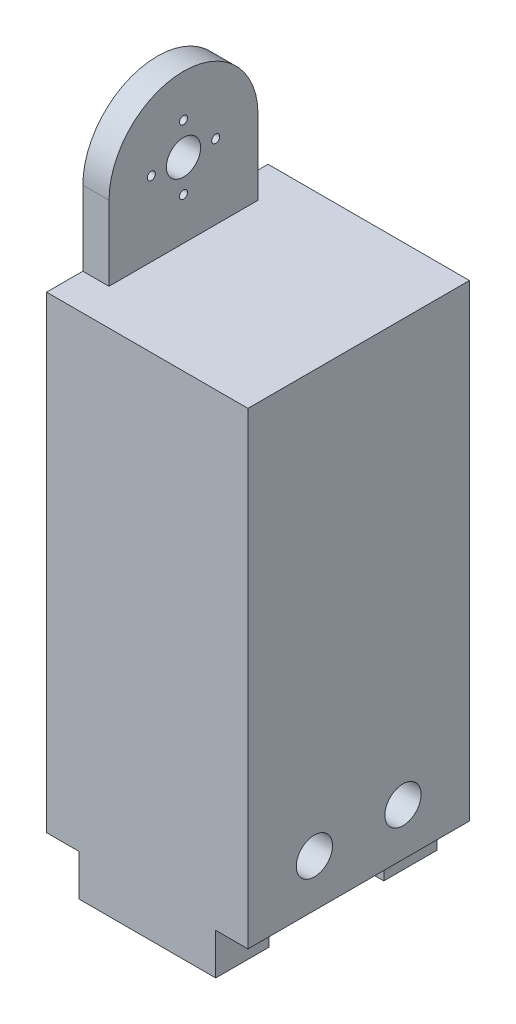
SolidWorks part; units mm, degrees
ref_plane "Front Plane" through (0, 0, 0) normal (0, 0, 1) x (1, 0, 0)
ref_plane "Top Plane" through (0, 0, 0) normal (0, 1, 0) x (1, 0, 0)
ref_plane "Right Plane" through (0, 0, 0) normal (1, 0, 0) x (0, 0, -1)
sketch "Sketch1" plane through (0, 0, 0) normal (0, 0, 1) x (1, 0, 0)
  line L1 (-25, 0) -> (25, 0)
  line L2 (-25, 0) -> (-25, -150)
  line L3 (-25, -150) -> (25, -150)
  line L4 (25, 0) -> (25, -150)
  dimension "D1" = 50
  dimension "D2" = 150
extrude "Boss-Extrude1" add sketch "Sketch1" against normal blind 55
sketch "Sketch2" plane through (25, 0, 0) normal (1, 0, 0) x (0, 0, -1)
  line L0 (55, 0) -> (0, 0) construction
  line L1 (0, -150) -> (0, 0) construction
  circle A0 centre (27.5, -25) radius 10.25
  dimension "D1" = 25
  dimension "D2" = 27.5
extrude "Cut-Extrude1" cut sketch "Sketch2" against normal blind 45 and the other way through all
sketch "Sketch7" plane through (-20, 0, 0) normal (1, 0, 0) x (0, 0, -1)
  line L0 (27.5, -17) -> (27.5, -33) construction
  circle A0 centre (27.5, -25) radius 8
  circle A1 centre (27.5, -17) radius 1
  circle A2 centre (35.5, -25) radius 1
  circle A3 centre (27.5, -33) radius 1
  circle A4 centre (19.5, -25) radius 1
  circle A5 centre (27.5, -25) radius 4.25
  point P14 (27.5, -25)
  dimension "D1" = 16
  dimension "D2" = 2
  dimension "D4" = 8.5
  dimension "D3" = 4
extrude "Cut-Extrude3" cut sketch "Sketch7" against normal blind 10 contours L0 A0 A1 | A0 A1 | A0 L0 A1 | A0 A4 | A0 A4 | L0 A3 A0 | A3 L0 A0 | A0 A3 | A0 A2 | A0 A2 | A5 L0 | L0 A5
sketch "Sketch8" plane through (25, 0, 0) normal (1, 0, 0) x (0, 0, -1)
  line L1 (55, -150) -> (55, 0) construction
  line L3 (0, -150) -> (55, -150)
  line L4 (0, -150) -> (0, -205)
  line L5 (0, -205) -> (55, -205)
  line L6 (55, -150) -> (55, -205)
  circle A1 centre (27.5, -180) radius 10.25
  circle A3 centre (27.5, -25) radius 10.25 construction
  dimension "D1" = 27.5
  dimension "D2" = 155
  dimension "D3" = 25
extrude "Boss-Extrude2" add sketch "Sketch8" against normal blind 50
sketch "Sketch10" plane through (0, 0, 0) normal (0, 0, 1) x (1, 0, 0)
  line L0 (-25, -205) -> (25, -205) construction
  line L5 (17, -205) -> (-17, -205)
  line L6 (17, -205) -> (17, -144.75)
  line L8 (-17, -205) -> (-17, -144.75)
  line L9 (-25, 0) -> (-25, -205) construction
  line L10 (-25, -180) -> (25, -180)
  line L13 (25, -169.75) -> (-25, -169.75)
  line L14 (25, -169.75) -> (25, -190.25)
  line L15 (25, -190.25) -> (-25, -190.25)
  line L16 (-25, -169.75) -> (-25, -190.25)
  line L17 (25, -205) -> (25, 0) construction
  line L18 (0, -180) -> (17, -180)
  line L19 (0, -180) -> (0, -191.25)
  line L20 (0, -191.25) -> (17, -191.25)
  line L21 (17, -180) -> (17, -191.25)
  line L22 (17, -191.25) -> (-17, -191.25)
  line L23 (17, -191.25) -> (17, -169.75)
  line L24 (17, -169.75) -> (-17, -169.75)
  line L25 (-17, -191.25) -> (-17, -169.75)
  line L26 (17, -191.25) -> (-17, -191.25)
  line L27 (17, -191.25) -> (17, -144.75)
  line L28 (17, -144.75) -> (-17, -144.75)
  line L29 (-17, -191.25) -> (-17, -144.75)
  line L30 (-25, -169.75) -> (-17, -169.75)
  line L31 (-25, -169.75) -> (-25, -205)
  line L32 (-25, -205) -> (-17, -205)
  line L33 (-17, -169.75) -> (-17, -205)
  line L34 (25, -169.75) -> (17, -169.75)
  line L35 (25, -169.75) -> (25, -205)
  line L36 (25, -205) -> (17, -205)
  line L37 (17, -169.75) -> (17, -205)
  line L38 (-25, -169.75) -> (25, -169.75)
  line L39 (-25, -169.75) -> (-25, -164.75)
  line L40 (-25, -164.75) -> (25, -164.75)
  line L41 (25, -169.75) -> (25, -164.75)
  line M7 (-25, 0) -> (-25, -205)
  line M8 (-25, -205) -> (25, -205)
  line M9 (25, -205) -> (25, 0)
  dimension "D1" = 8
  dimension "D2" = 8
  dimension "D3" = 11.25
  dimension "D4" = 46.5
  dimension "D5" = 60.25
  dimension "D6" = 5
extrude "Cut-Extrude4" cut sketch "Sketch10" against normal through all contours L20 L22 L8 L6 M8 | L8 L15 M7 M8 | L15 L6 M9 M8 | L15 L8 L10 M7 | L8 L13 L10 M7 | L13 L6 L10 M9 | L15 L10 L6 M9 | L19 L10 L8 L15 | L10 L19 L15 L6 | L6 L13 L8 L10 | L22 L19 L15 L8 | L19 L20 L6 L15 | L29 L40 L27 L28 | L40 L8 L13 L6
sketch "Sketch11" plane through (0, -144.75, 0) normal (0, -1, 0) x (1, 0, 0)
  line L0 (17, -55) -> (17, 0) construction
  line L1 (-17, 0) -> (17, 0)
  line L2 (-17, 0) -> (-17, -13.25)
  line L3 (-17, -13.25) -> (17, -13.25)
  line L4 (17, 0) -> (17, -13.25)
  line L5 (25, -27.5) -> (-30.9131, -27.5) construction
  line L6 (25, -55) -> (25, 0) construction
  line L7 (17, -55) -> (17, -41.75)
  line L8 (-17, -41.75) -> (17, -41.75)
  line L9 (-17, -55) -> (-17, -41.75)
  line L10 (-17, -55) -> (17, -55)
  dimension "D1" = 14.25
extrude "Boss-Extrude4" add sketch "Sketch11" along normal blind 25
sketch "Sketch13" plane through (25, 0, 0) normal (1, 0, 0) x (0, 0, -1)
  line L0 (0, -169.75) -> (0, 0) construction
  line L1 (55, -169.75) -> (0, -169.75)
  line L2 (55, -169.75) -> (55, -159.75)
  line L3 (55, -159.75) -> (0, -159.75)
  line L4 (0, -169.75) -> (0, -159.75)
  dimension "D1" = 10
extrude "Cut-Extrude5" cut sketch "Sketch13" against normal blind 8
ref_plane "Plane2" through (0, 0, 0) normal (1, 0, 0) x (0, 0, -1)
mirror "Mirror2" about plane through (0, 0, 0) normal (1, 0, 0) of "Cut-Extrude5"
sketch "Sketch14" plane through (25, 0, 0) normal (1, 0, 0) x (0, 0, -1)
  line L0 (55, -159.75) -> (0, -159.75) construction
  line L1 (0, -159.75) -> (0, 0) construction
  circle A1 centre (16.5, -148) radius 5.0302
  circle A2 centre (38.5, -148) radius 5.0302
  dimension "D1" = 16.5
  dimension "D2" = 2
  dimension "D3" = 11.75
extrude "Cut-Extrude6" cut sketch "Sketch14" against normal blind 8
mirror "Mirror3" about plane through (0, 0, 0) normal (1, 0, 0) of "Cut-Extrude6"
sketch "Sketch15" plane through (0, 0, 0) normal (0, 0, 1) x (1, 0, 0)
  line L0 (-25, 0) -> (25, 0)
  line L1 (25, 0) -> (0, 0)
  line L3 (-17, -169.75) -> (17, -169.75)
  line L4 (-17, -169.75) -> (-17, -170)
  line L5 (-17, -170) -> (17, -170)
  line L6 (17, -169.75) -> (17, -170)
  line M5 (-17, -169.75) -> (17, -169.75)
  dimension "D1" = 0.25
extrude "Boss-Extrude5" add sketch "Sketch15" against normal blind 13.25 contours L6 L4 L5 M5
ref_plane "Plane3" through (0, 0, -27.5) normal (0, 0, 1) x (1, 0, 0)
mirror "Mirror4" about plane through (0, 0, -27.5) normal (0, 0, 1) of "Boss-Extrude5"
sketch "Sketch16" plane through (0, 0, 0) normal (0, 0, 1) x (1, 0, 0)
  line L7 (-20, -14.75) -> (-18.5, -14.75)
  line L8 (-20, -14.75) -> (-20, -35.25)
  line L9 (-20, -35.25) -> (-18.5, -35.25)
  line L10 (-18.5, -14.75) -> (-18.5, -35.25)
  line L11 (25, 0) -> (-18.5, 0)
  line L12 (25, 0) -> (25, -43.5)
  line L13 (25, -43.5) -> (-18.5, -43.5)
  line L14 (-18.5, 0) -> (-18.5, -43.5)
  line M12 (25, -159.75) -> (25, 0)
  line M13 (25, 0) -> (-25, 0)
  dimension "D1" = 1.5
  dimension "D2" = 43.5
  dimension "D3" = 43.5
extrude "Cut-Extrude7" cut sketch "Sketch16" against normal through all contours L14 L10 L13 M13 M12
sketch "Sketch19" plane through (-20, 0, 0) normal (1, 0, 0) x (0, 0, -1)
  circle A0 centre (27.5, -25) radius 4.25
  circle A1 centre (35.5, -25) radius 1
  circle A2 centre (27.5, -33) radius 1
  circle A3 centre (19.5, -25) radius 1
  circle A4 centre (27.5, -17) radius 1
  point P15 (27.5, -25)
  circle M5 centre (27.5, -25) radius 4.25
  circle M6 centre (27.5, -17) radius 1
  circle M7 centre (35.5, -25) radius 1
  circle M8 centre (27.5, -33) radius 1
  circle M9 centre (19.5, -25) radius 1
  circle M10 centre (27.5, -25) radius 10.25
  dimension "D1" = 4
extrude "Boss-Extrude6" add sketch "Sketch19" along normal blind 1.5 contours M10 M6 M8 M9 M7 M5
sketch "Sketch20" plane through (-18.5, 0, 0) normal (1, 0, 0) x (0, 0, -1)
  line L0 (0, -43.5) -> (9, -43.5)
  line L1 (9, -25) -> (9, -43.5)
  line L2 (9, -43.5) -> (0, -43.5)
  line L3 (46, -25) -> (46, -43.5)
  line L4 (46, -43.5) -> (55, -43.5)
  line L5 (46, -43.5) -> (55, -43.5)
  line L7 (9, -43.5) -> (0, -43.5)
  line L8 (9, -43.5) -> (9, -25)
  line L12 (9, -25) -> (9, -43.5)
  line L13 (9, -43.5) -> (0, -43.5)
  line L15 (0, 0) -> (55, 0)
  line L16 (0, 0) -> (0, -43.5)
  line L17 (0, -43.5) -> (55, -43.5)
  line L18 (55, 0) -> (55, -43.5)
  circle A0 centre (27.5, -25) radius 18.5
  line M6 (0, 0) -> (0, -43.5)
  line M7 (0, -43.5) -> (55, -43.5)
  line M8 (55, -43.5) -> (55, 0)
  line M9 (55, 0) -> (0, 0)
extrude "Cut-Extrude8" cut sketch "Sketch20" against normal through all contours A0 L3 L1 M7 M8 M9 M6
sketch "Sketch21" plane through (25, 0, 0) normal (1, 0, 0) x (0, 0, -1)
  circle A0 centre (16.5, -148) radius 5.0302
  circle A1 centre (16.5, -148) radius 4.5
  circle A2 centre (38.5, -148) radius 4.5
  circle A3 centre (38.5, -148) radius 5.0302
  dimension "D1" = 2
extrude "Boss-Extrude7" add sketch "Sketch21" against normal blind 8
mirror "Mirror5" about plane through (0, 0, 0) normal (1, 0, 0) of "Boss-Extrude7"
